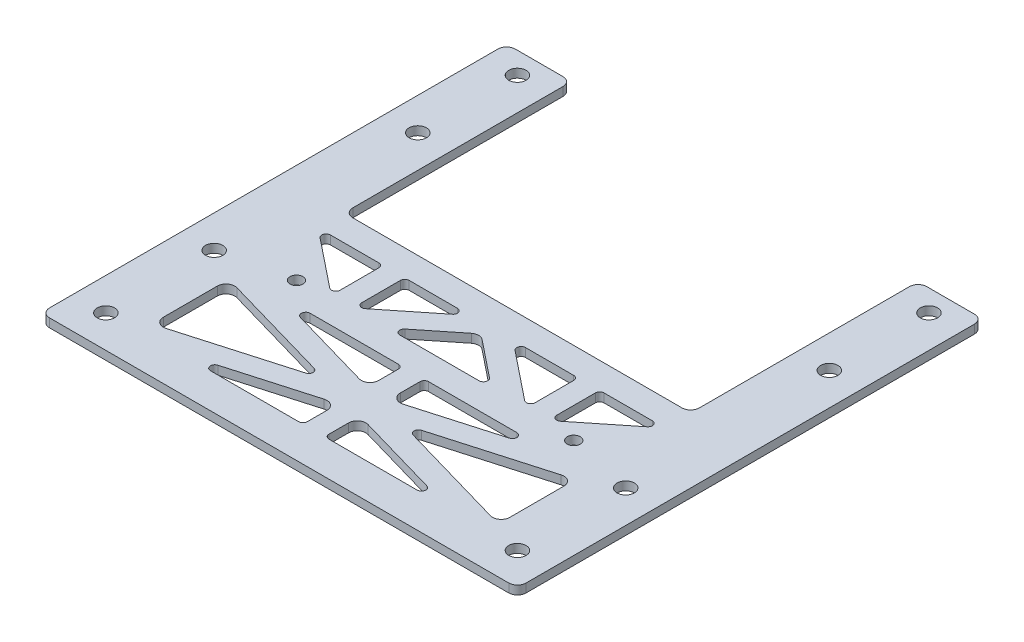
SolidWorks part; units mm, degrees
material "Thornel Mat VMA"
ref_plane "前视基准面" through (0, 0, 0) normal (0, 0, 1) x (1, 0, 0)
ref_plane "上视基准面" through (0, 0, 0) normal (0, 1, 0) x (1, 0, 0)
ref_plane "右视基准面" through (0, 0, 0) normal (1, 0, 0) x (0, 0, -1)
sketch "草图1" plane through (0, 0, 0) normal (0, 1, 0) x (1, 0, 0)
  line L0 (55, 107.5) -> (55, 0)
  line L2 (47.5, 7.5) -> (47.5, 107.5) construction
  line L5 (40, 107.5) -> (40, 55)
  line L9 (40, 107.5) -> (55, 107.5)
  line L11 (-55, 0) -> (55, 0)
  line L21 (40, 55) -> (-40, 55)
  line L22 (0, -55) -> (0, 55) construction
  line L23 (-47.5, 7.5) -> (-47.5, 107.5) construction
  line L24 (-40, 107.5) -> (-55, 107.5)
  line L25 (-40, 107.5) -> (-40, 55)
  line L26 (-55, 107.5) -> (-55, 0)
  line L27 (-32, 36) -> (32, 36) construction
  circle A0 centre (47.5, 32.5) radius 2
  circle A1 centre (47.5, 7.5) radius 2
  circle A2 centre (47.5, 79.5) radius 2
  circle A4 centre (47.5, 102.5) radius 2
  circle A5 centre (-47.5, 102.5) radius 2
  circle A6 centre (-47.5, 79.5) radius 2
  circle A7 centre (-47.5, 7.5) radius 2
  circle A8 centre (-47.5, 32.5) radius 2
  circle A9 centre (-32, 36) radius 1.5
  circle A11 centre (32, 36) radius 1.5
  point P32 (0, 0)
  dimension "D4" = 7.5
  dimension "D3" = 4
  dimension "D5" = 47
  dimension "D7" = 23
  dimension "D10" = 5
  dimension "D9" = 3
  dimension "D1" = 25
  dimension "D2" = 95
  dimension "D6" = 55
  dimension "D8" = 36
  dimension "D11" = 15
  dimension "D12" = 64
extrude "凸台-拉伸1" add sketch "草图1" along normal blind 2
sketch "草图2" plane through (0, 2, 0) normal (0, 1, 0) x (1, 0, 0)
  line L1 (-40, 31) -> (40, 31)
  line L2 (-40, 31) -> (-40, 8)
  line L3 (-40, 8) -> (40, 8)
  line L4 (40, 31) -> (40, 8)
  line L5 (-55, 0) -> (55, 0) construction
  line L6 (-40, 55) -> (-40, 107.5) construction
  line L7 (40, 107.5) -> (40, 55) construction
  line L8 (-40, 49) -> (-25, 37)
  line L9 (-25, 37) -> (-25, 49)
  line L10 (-25, 49) -> (-40, 49)
  line L11 (-20, 49) -> (-5, 49)
  line L12 (-5, 49) -> (-20, 37)
  line L13 (-20, 37) -> (-20, 49)
  line L14 (0, 46.5969) -> (-11.9961, 37)
  line L15 (-11.9961, 37) -> (11.9961, 37)
  line L16 (40, 55) -> (-40, 55) construction
  line L17 (0, -1.1) -> (0, 1.1) construction
  line L18 (0, 46.5969) -> (11.9961, 37)
  line L19 (20, 37) -> (20, 49)
  line L20 (5, 49) -> (20, 37)
  line L21 (20, 49) -> (5, 49)
  line L22 (25, 49) -> (40, 49)
  line L23 (25, 37) -> (25, 49)
  line L24 (40, 49) -> (25, 37)
  circle A0 centre (-32, 36) radius 1.5 construction
  point P16 (0, 0)
  point P18 (0, 47.2423)
  point P19 (0, 43.7502)
  point P24 (0, 47.7855)
  point P25 (13.4732, 37)
  dimension "D1" = 5
  dimension "D2" = 8
  dimension "D3" = 6
  dimension "D4" = 5
  dimension "D5" = 5
  dimension "D6" = 6
  dimension "D7" = 15
extrude "切除-拉伸1" cut sketch "草图2" against normal through all
sketch "草图3" plane through (0, 2, 0) normal (0, 1, 0) x (1, 0, 0)
  line L0 (-40, 31) -> (40, 8)
  line L1 (-40, 8) -> (40, 31)
  line L2 (0, 31) -> (0, 8)
  line L3 (40, 31) -> (-40, 31) construction
  line L4 (-40, 8) -> (40, 8) construction
extrude "拉伸-薄壁2" add sketch "草图3" against normal up to surface (2 mm away) thin up to face at (0, 0, -19.5) thin type mid plane wall 5
fillet "圆角1" radius 2 8 edges at (55, 1, -107.5) (55, 1, 0) (-55, 1, 0) (-55, 1, -107.5) (-40, 1, -107.5) (-40, 1, -55) (40, 1, -55) (40, 1, -107.5)
fillet "圆角2" radius 1 24 edges at (25, 1, -49) (40, 1, -49) (25, 1, -37) (-5, 1, -49) (-20, 1, -37) (5, 1, -49) (20, 1, -49) (20, 1, -37) (-11.9961, 1, -37) (11.9961, 1, -37) (-2.5, 1, -31) (-30.9521, 1, -31) (-2.5, 1, -8) (-30.9521, 1, -8) (2.5, 1, -31) (30.9521, 1, -31) (-9.0479, 1, -19.5) (9.0479, 1, -19.5) (2.5, 1, -8) (30.9521, 1, -8) (-20, 1, -49) (-25, 1, -49) (-25, 1, -37) (-40, 1, -49)
fillet "圆角3" radius 2 9 edges at (2.5, 1, -22.82) (2.5, 1, -16.18) (-2.5, 1, -16.18) (-2.5, 1, -22.82) (-40, 1, -10.6013) (-40, 1, -28.3987) (40, 1, -10.6013) (0, 1, -46.5969) (40, 1, -28.3987)
